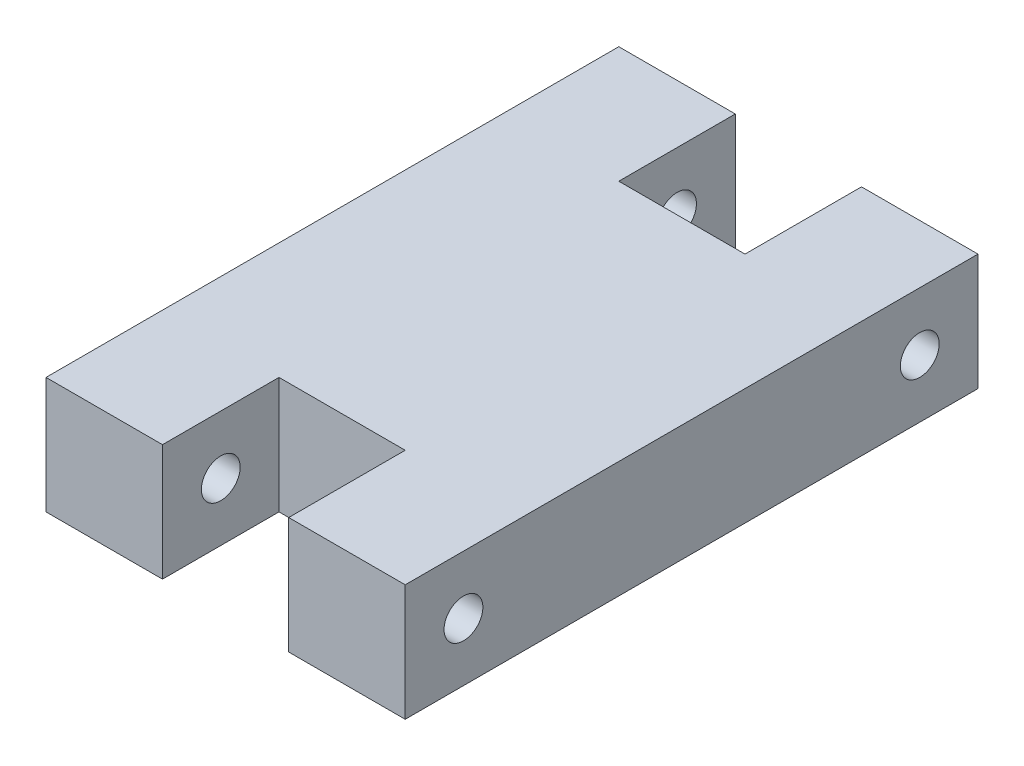
SolidWorks part; units mm, degrees
material "Beech"
ref_plane "Front Plane" through (0, 0, 0) normal (0, 0, 1) x (1, 0, 0)
ref_plane "Top Plane" through (0, 0, 0) normal (0, 1, 0) x (1, 0, 0)
ref_plane "Right Plane" through (0, 0, 0) normal (1, 0, 0) x (0, 0, -1)
sketch "Sketch1" plane through (0, 0, 0) normal (0, 1, 0) x (1, 0, 0)
  line L1 (-18.5, -29.5) -> (18.5, -29.5)
  line L2 (-18.5, -29.5) -> (-18.5, 29.5)
  line L3 (-18.5, 29.5) -> (18.5, 29.5)
  line L4 (18.5, -29.5) -> (18.5, 29.5)
  line L5 (-18.5, -29.5) -> (18.5, 29.5) construction
  line L6 (-18.5, 29.5) -> (18.5, -29.5) construction
  point P0 (0, 0)
  dimension "D1" = 59
  dimension "D2" = 37
extrude "Boss-Extrude1" add sketch "Sketch1" along normal blind 12
sketch "Sketch2" plane through (0, 12, 0) normal (0, 1, 0) x (1, 0, 0)
  line L0 (18.5, 29.5) -> (-18.5, 29.5) construction
  line L1 (-6.5, 29.5) -> (6.5, 29.5)
  line L2 (-6.5, 29.5) -> (-6.5, 17.5)
  line L3 (-6.5, 17.5) -> (6.5, 17.5)
  line L4 (6.5, 29.5) -> (6.5, 17.5)
  line L5 (-18.5, -29.5) -> (18.5, -29.5) construction
  line L6 (-6.5, -29.5) -> (6.5, -29.5)
  line L7 (-6.5, -29.5) -> (-6.5, -17.5)
  line L8 (-6.5, -17.5) -> (6.5, -17.5)
  line L9 (6.5, -29.5) -> (6.5, -17.5)
  line L10 (-18.5, 29.5) -> (-18.5, -29.5) construction
  line L11 (18.5, -29.5) -> (18.5, 29.5) construction
  dimension "D1" = 12
  dimension "D2" = 12
  dimension "D3" = 12
  dimension "D4" = 12
  dimension "D5" = 12
  dimension "D6" = 12
extrude "Cut-Extrude1" cut sketch "Sketch2" against normal up to next
sketch "Sketch3" plane through (-18.5, 0, 0) normal (-1, 0, 0) x (0, 0, 1)
  line L0 (-29.5, 12) -> (29.5, 12) construction
  line L1 (-29.5, 12) -> (-29.5, 0) construction
  circle A0 centre (-23.5, 6) radius 2
  dimension "D2" = 4
  dimension "D1" = 6
  dimension "D3" = 6
extrude "Cut-Extrude2" cut sketch "Sketch3" against normal up to surface (37 mm away) up to face at (18.5, 6, 0)
mirror "Mirror1" about plane through (0, 0, 0) normal (0, 0, 1) of "Cut-Extrude2"
